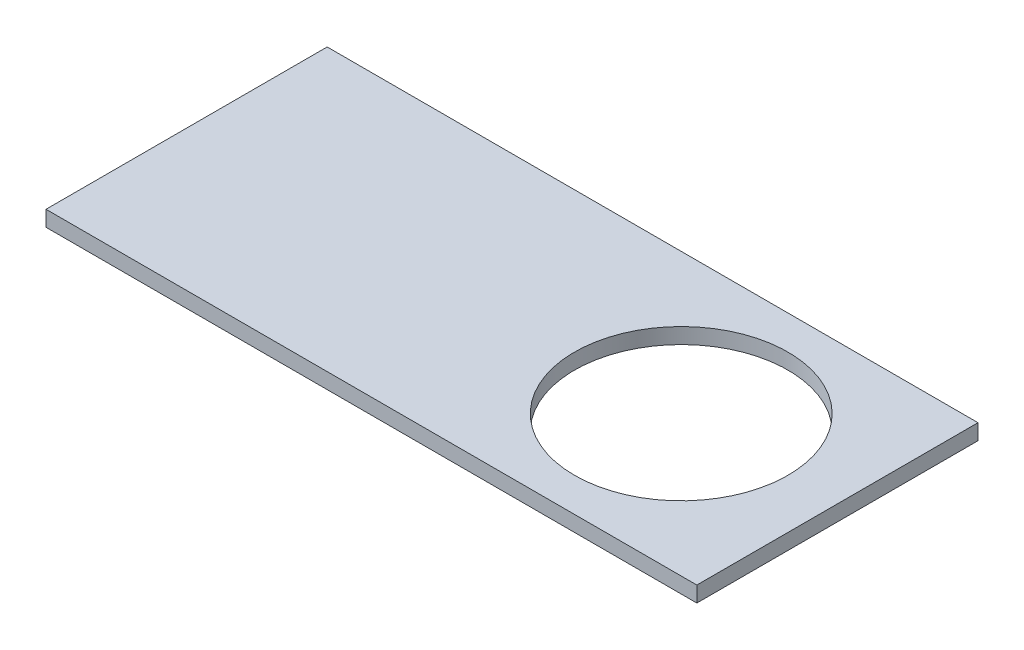
SolidWorks part; units mm, degrees
material "Сталь 3 ГОСТ 535-88"
ref_plane "Спереди" through (0, 0, 0) normal (0, 0, 1) x (1, 0, 0)
ref_plane "Сверху" through (0, 0, 0) normal (0, 1, 0) x (1, 0, 0)
ref_plane "Справа" through (0, 0, 0) normal (1, 0, 0) x (0, 0, -1)
sketch "Эскиз1" plane through (0, 0, 0) normal (0, 1, 0) x (1, 0, 0)
  line L1 (-125, -54) -> (125, -54)
  line L2 (-125, -54) -> (-125, 54)
  line L3 (-125, 54) -> (125, 54)
  line L4 (125, -54) -> (125, 54)
  line L5 (0, 54) -> (0, -54) construction
  line L6 (-125, 0) -> (125, 0) construction
  circle A0 centre (65, 0) radius 41
  point P0 (0, 0)
  dimension "D3" = 82
  dimension "D1" = 250
  dimension "D2" = 108
  dimension "D4" = 60
extrude "Бобышка-Вытянуть1" add sketch "Эскиз1" along normal blind 6
